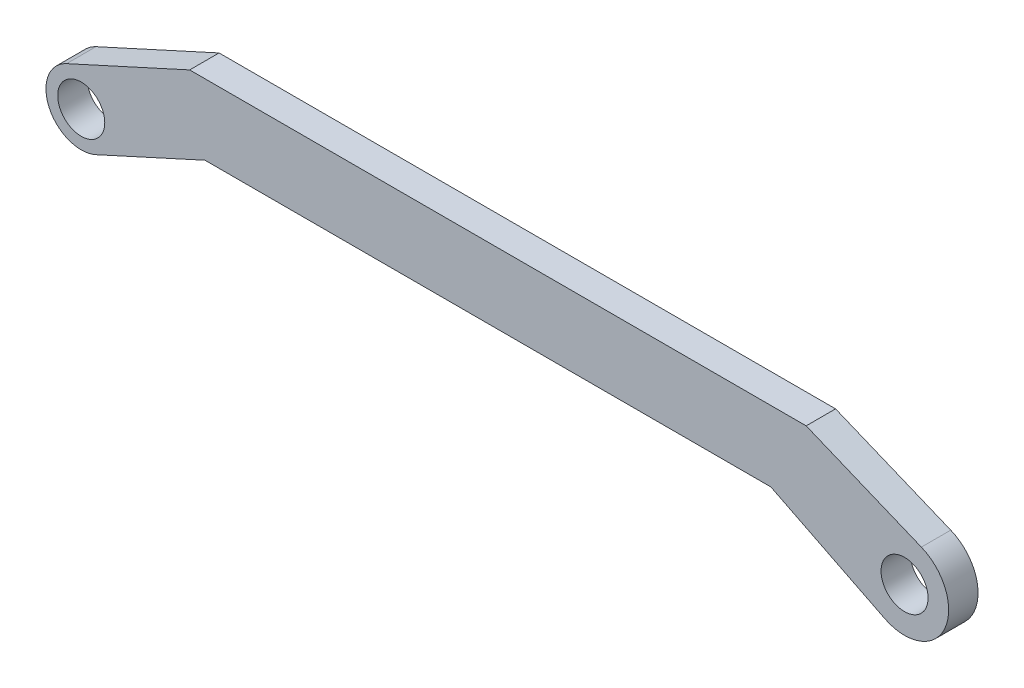
SolidWorks part; units mm, degrees
ref_plane "Piano frontale" through (0, 0, 0) normal (0, 0, 1) x (1, 0, 0)
ref_plane "Piano superiore" through (0, 0, 0) normal (0, 1, 0) x (1, 0, 0)
ref_plane "Piano destro" through (0, 0, 0) normal (1, 0, 0) x (0, 0, -1)
sketch "Schizzo1" plane through (0, 0, 0) normal (0, 0, 1) x (1, 0, 0)
  line L0 (0, 0) -> (4, 0) construction
  line L1 (0, 0) -> (4, 0) construction
  line L2 (18.4401, 15) -> (123.2697, 15)
  line L3 (18.4401, 15) -> (-2.4887, 5.4595)
  line L4 (117.2602, 3) -> (136.6416, -6.7061)
  line L5 (0, 15) -> (180, 15) construction
  line L6 (123.2697, 15) -> (142.8557, 6.9351)
  line L7 (21.0462, 3) -> (2.4887, -5.4595)
  line L8 (21.0462, 3) -> (117.2602, 3)
  line L10 (18.4401, 15) -> (153.6285, 15) construction
  line L11 (14.4651, 0) -> (136, 0) construction
  line L12 (0, 0) -> (180, 0) construction
  line L13 (153.6285, 15) -> (176.0501, 6.3756) construction
  line L14 (151.4002, 3) -> (171.7421, -4.8244) construction
  line L15 (21.0462, 3) -> (151.4002, 3) construction
  circle A0 centre (0, 0) radius 4
  circle A1 centre (140, 0) radius 4
  arc A2 (136.6416, -6.7061) -> (142.8557, 6.9351) centre (140, 0) ccw
  arc A5 (-2.4887, 5.4595) -> (2.4887, -5.4595) centre (0, 0) ccw
  arc A6 (174.4098, -5) -> (176.0501, 6.3756) centre (180, 0) ccw construction
  arc A7 (171.7421, -4.8244) -> (171.7421, -4.8244) centre (171.7421, -4.8244) cw construction
  dimension "D1" = 8
  dimension "D2" = 8
  dimension "D4" = 15
  dimension "D5" = 12
  dimension "D3" = 140
  dimension "D6" = 15
extrude "Estrusione-Estrusione1" add sketch "Schizzo1" along normal blind 5
